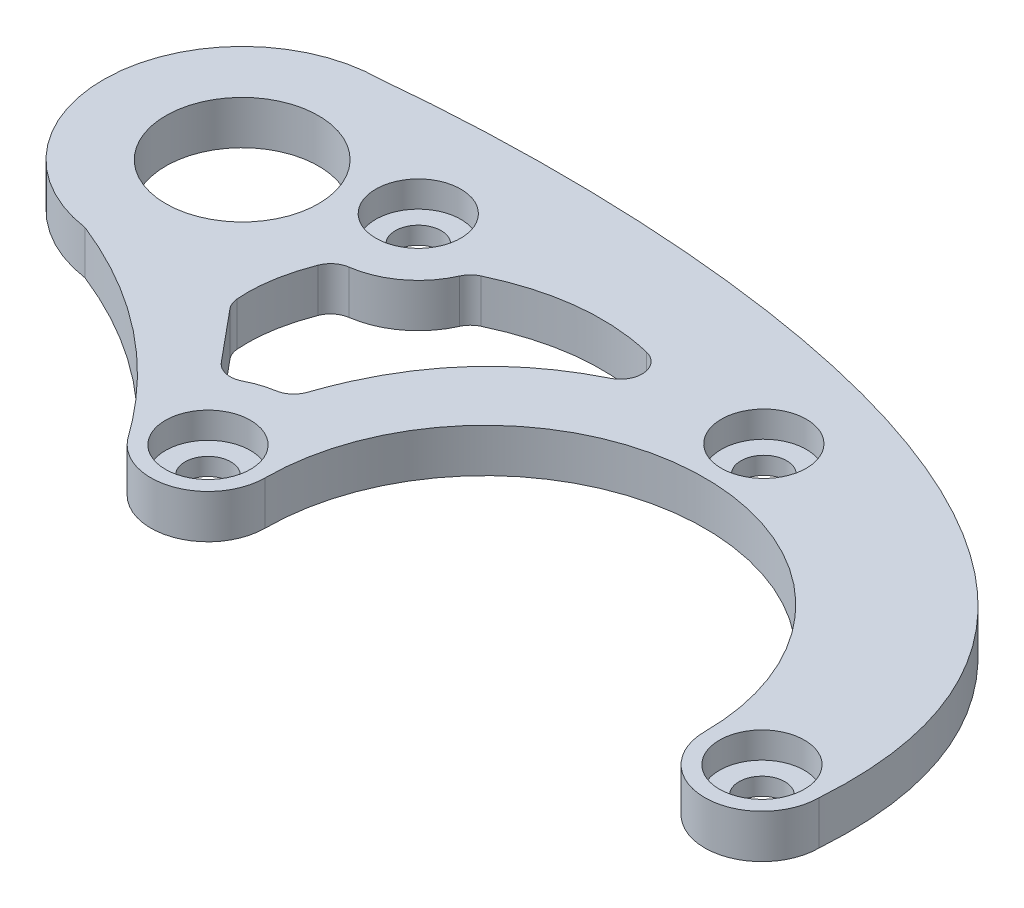
SolidWorks part; units mm, degrees
ref_plane "Front" through (0, 0, 0) normal (0, 0, 1) x (1, 0, 0)
ref_plane "Top" through (0, 0, 0) normal (0, 1, 0) x (1, 0, 0)
ref_plane "Right" through (0, 0, 0) normal (1, 0, 0) x (0, 0, -1)
sketch "Sketch1" plane through (0, 0, 0) normal (0, 1, 0) x (1, 0, 0)
  line L0 (-35.5828, 12.2797) -> (-30.1874, 5.7733)
  circle A3 centre (-46.4745, 24.2108) radius 7
  arc A12 (20.1562, 0) -> (-20.1562, 0) centre (0, 0) ccw
  circle A13 centre (-25.4, 0) radius 2.1
  circle A14 centre (25.4, 0) radius 2.1
  arc A15 (-29.7806, -2.8822) -> (-20.1562, 0) centre (-25.4, 0) ccw
  arc A16 (20.1562, 0) -> (30.6438, 0) centre (25.4, 0) ccw
  arc A17 (-46.4745, 36.9348) -> (-48.2765, 11.6151) centre (-46.4745, 24.2108) ccw
  circle A18 centre (0, 25.5713) radius 2.1
  circle A22 centre (-34.1163, 28.0012) radius 2.1
  arc A23 (-34.1163, 20.5012) -> (-27.0209, 25.5713) centre (-34.1163, 28.0012) ccw
  arc A24 (-25.4, 7.5) -> (-30.1874, 5.7733) centre (-25.4, 0) ccw
  spline S0 degree 3 poles (-48.2765, 11.6151) (-40.6637, 8.5838) (-34.415, 3.6353) (-29.5304, -3.2306) knots 0.158174 0.158174 0.158174 0.158174 1 1 1 1
  spline S1 degree 3 poles (-46.4745, 36.9348) (-23.1642, 39.3519) (33.3739, 38.1202) (30.6438, 0) knots 0 0 0 0 1 1 1 1
  spline S2 degree 2 poles (-27.0209, 25.5713) (-17.4026, 30.4955) (-7.5, 25.5713) knots 0 0 0 1 1 1
  spline S3 degree 3 poles (-34.1163, 20.5012) (-35.4383, 17.6517) (-35.9272, 14.9112) (-35.5828, 12.2797) knots 0 0 0 0 0.482948 0.482948 0.482948 0.482948
  spline S4 degree 2 poles (-7.5, 25.5713) (-21.2937, 21.4574) (-25.4, 7.5) knots 0 0 0 1 1 1
  point P0 (0, 0)
  point P9 (0, 0)
  point P39 (0, 0)
  dimension "D2" = 4.2
  dimension "D3" = 4.2
  dimension "D4" = 4.2
  dimension "D1" = 14
  dimension "D5" = 50.8
  dimension "D6" = 4.2
extrude "Boss-Extrude1" add sketch "Sketch1" along normal blind 4
fillet "Fillet1" radius 2 6 edges at (-34.1163, 2, -20.5012) (-35.5828, 2, -12.2797) (-30.1874, 2, -5.7733) (-25.4, 2, -7.5) (-7.5, 2, -25.5713) (-27.0209, 2, -25.5713)
sketch "Sketch2" plane through (0, 4, 0) normal (0, 1, 0) x (1, 0, 0)
  circle A0 centre (-34.1163, 28.0012) radius 3.9
  circle A1 centre (0, 25.5713) radius 3.9
  circle A2 centre (-25.4, 0) radius 3.9
  circle A3 centre (25.4, 0) radius 3.9
extrude "Cut-Extrude1" cut sketch "Sketch2" against normal blind 2.4
